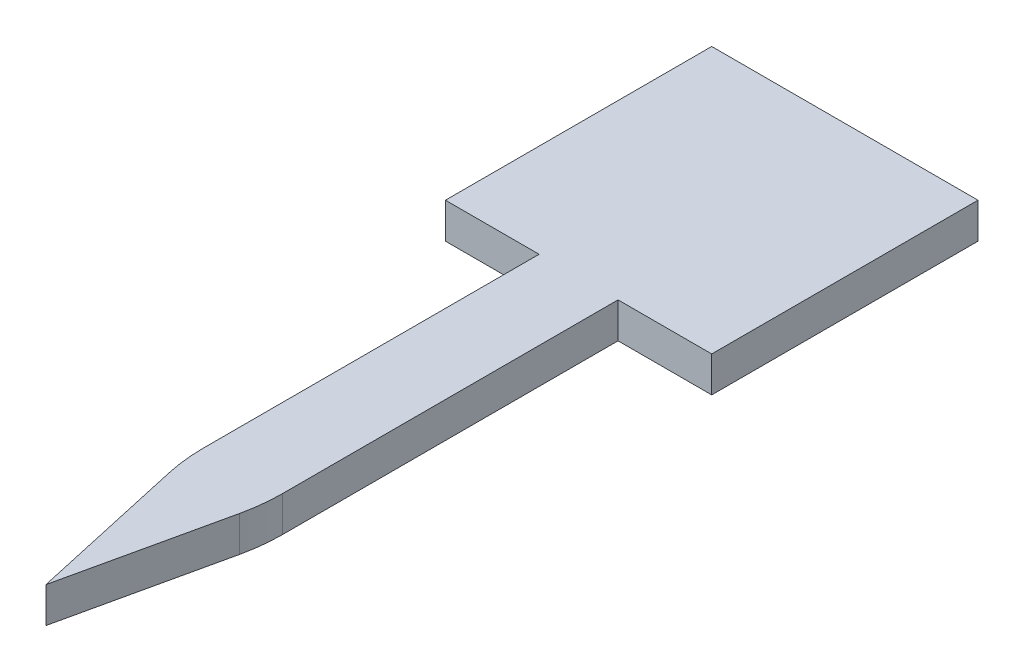
SolidWorks part; units mm, degrees
ref_plane "Ön Düzlem" through (0, 0, 0) normal (0, 0, 1) x (1, 0, 0)
ref_plane "Üst Düzlem" through (0, 0, 0) normal (0, 1, 0) x (1, 0, 0)
ref_plane "Sağ Düzlem" through (0, 0, 0) normal (1, 0, 0) x (0, 0, -1)
sketch "Çizim1" plane through (0, 0, 0) normal (0, 1, 0) x (1, 0, 0)
  line L1 (-7.5, -7.5) -> (7.5, -7.5)
  line L2 (-7.5, -7.5) -> (-7.5, 7.5)
  line L3 (-7.5, 7.5) -> (7.5, 7.5)
  line L4 (7.5, -7.5) -> (7.5, 7.5)
  line L5 (-7.5, -7.5) -> (7.5, 7.5) construction
  line L6 (-7.5, 7.5) -> (7.5, -7.5) construction
  point P0 (0, 0)
extrude "Yükseklik-Ekstrüzyon1" add sketch "Çizim1" along normal blind 2
sketch "Çizim2" plane through (0, 0, 7.5) normal (0, 0, 1) x (1, 0, 0)
  line L0 (0, 2) -> (0, 0)
  line L1 (-7.5, 2) -> (7.5, 2) construction
  line L2 (-7.5, 0) -> (7.5, 0) construction
  line L3 (-2.2242, 2) -> (2.2242, 2)
  line L4 (-2.2242, 2) -> (-2.2242, 0)
  line L5 (-2.2242, 0) -> (2.2242, 0)
  line L6 (2.2242, 2) -> (2.2242, 0)
  line L7 (-2.2242, 2) -> (2.2242, 0) construction
  line L8 (-2.2242, 0) -> (2.2242, 2) construction
  point P5 (0, 1)
  line M1 (-7.5, 0) -> (7.5, 0)
  line M3 (7.5, 2) -> (-7.5, 2)
extrude "Yükseklik-Ekstrüzyon2" add sketch "Çizim2" along normal blind 20 contours L6 L0 M3 M1 | L4 L0 M3 M1
sketch "Çizim3" plane through (0, 0, 0) normal (0, 1, 0) x (1, 0, 0)
  line L0 (-2.2242, -27.5) -> (2.2242, -27.5)
  line L2 (0, -37.5) -> (2.2242, -27.5)
  line L3 (0, -37.5) -> (-2.2242, -27.5)
extrude "Yükseklik-Ekstrüzyon3" add sketch "Çizim3" along normal blind 2
fillet "Radyus1" radius 10 1 edges at (-2.2242, 1, 27.5)
fillet "Radyus2" radius 10 1 edges at (2.2242, 1, 27.5)
